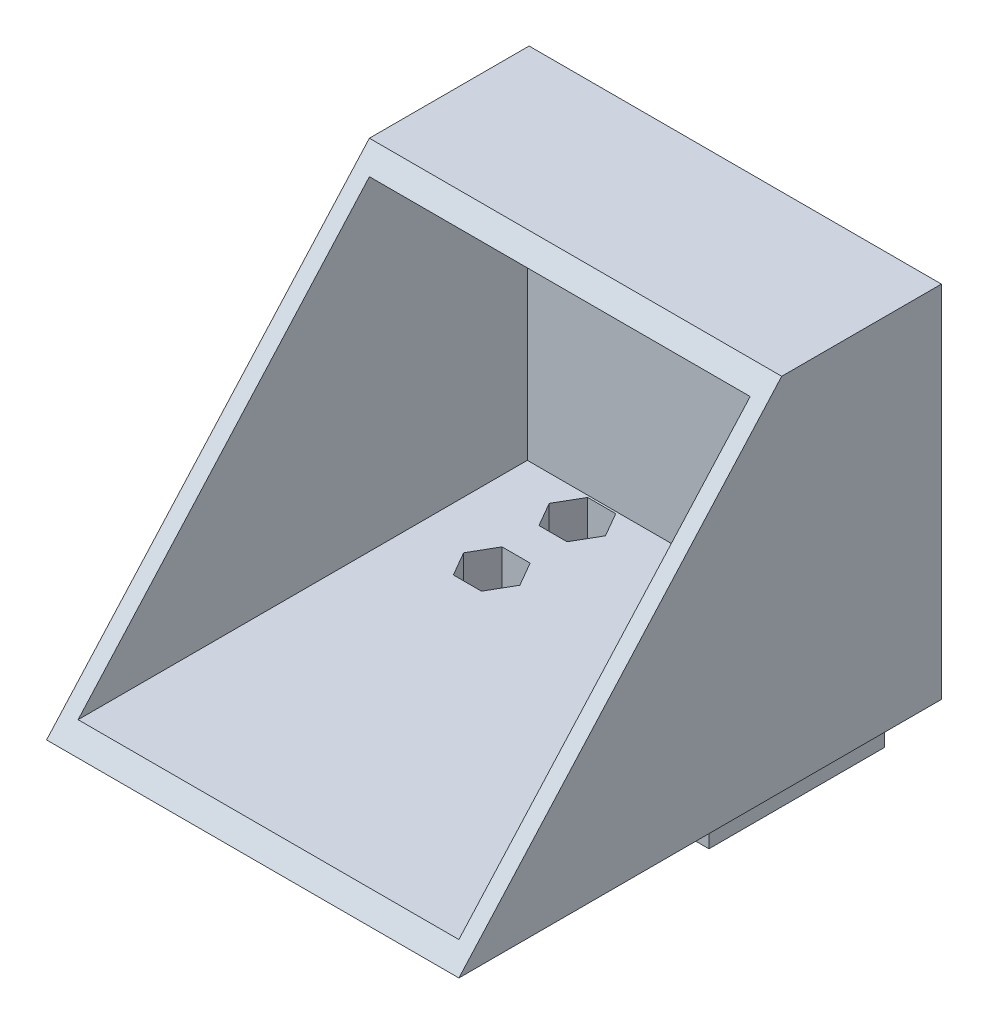
SolidWorks part; units mm, degrees
ref_plane "前视基准面" through (0, 0, 0) normal (0, 0, 1) x (1, 0, 0)
ref_plane "上视基准面" through (0, 0, 0) normal (0, 1, 0) x (1, 0, 0)
ref_plane "右视基准面" through (0, 0, 0) normal (1, 0, 0) x (0, 0, -1)
other "Configuration Table"
ref_plane "基准面1" through (21.7, 0, 0) normal (1, 0, 0) x (0, 0, -1)
sketch "草图1" plane through (21.7, 0, 0) normal (1, 0, 0) x (0, 0, -1)
  line L0 (-18.2051, 8) -> (-18.2051, 49)
  line L1 (-18.2051, 49) -> (-55, 8)
  line L2 (-55, 8) -> (-18.2051, 8)
extrude "凸台-拉伸1" add sketch "草图1" against normal blind 43.4
sketch "草图2" plane through (-21.7, 0, 0) normal (-1, 0, 0) x (0, 0, 1)
  line L0 (18.2051, 8) -> (18.2051, 49)
  line L1 (18.2051, 49) -> (55, 8)
  line L2 (55, 8) -> (18.2051, 8)
extrude "凸台-拉伸2" add sketch "草图2" along normal blind 1.8
sketch "草图3" plane through (21.7, 0, 0) normal (1, 0, 0) x (0, 0, -1)
  line L0 (-18.2051, 8) -> (-18.2051, 47)
  line L1 (-18.2051, 47) -> (-20, 47)
  line L2 (-20, 47) -> (-55, 8)
  line L3 (-55, 8) -> (-18.2051, 8)
extrude "切除-拉伸1" cut sketch "草图3" against normal blind 43.4
sketch "草图4" plane through (-21.7, 0, 0) normal (1, 0, 0) x (0, 0, -1)
  line L0 (-18.2051, 10) -> (-18.2051, 8)
  line L1 (-18.2051, 8) -> (-55, 8)
  line L2 (-55, 8) -> (-53.2051, 10)
  line L3 (-53.2051, 10) -> (-18.2051, 10)
extrude "凸台-拉伸3" add sketch "草图4" along normal blind 43.4
sketch "草图5" plane through (0, 0, 18.2051) normal (0, 0, -1) x (-1, 0, 0)
  line L0 (21.7, 10) -> (21.7, 47)
  line L1 (21.7, 47) -> (-21.7, 47)
  line L2 (-21.7, 47) -> (-21.7, 49)
  line L3 (-21.7, 49) -> (23.5, 49)
  line L4 (23.5, 49) -> (23.5, 8)
  line L5 (23.5, 8) -> (-21.7, 8)
  line L6 (-21.7, 8) -> (-21.7, 10)
  line L7 (-21.7, 10) -> (21.7, 10)
extrude "凸台-拉伸4" add sketch "草图5" along normal blind 16.2051
sketch "草图6" plane through (0, 0, 2) normal (0, 0, -1) x (-1, 0, 0)
  line L0 (-21.7, 8) -> (-21.7, 49)
  line L1 (-21.7, 49) -> (23.5, 49)
  line L2 (23.5, 49) -> (23.5, 8)
  line L3 (23.5, 8) -> (-21.7, 8)
extrude "凸台-拉伸5" add sketch "草图6" along normal blind 2
sketch "草图7" plane through (0, 8, 0) normal (0, -1, 0) x (1, 0, 0)
  line L0 (-17, 0) -> (-17, 20)
  line L1 (-17, 20) -> (17, 20)
  line L2 (17, 20) -> (17, 0)
  line L3 (17, 0) -> (-17, 0)
extrude "凸台-拉伸6" add sketch "草图7" along normal blind 8
sketch "草图10" plane through (21.7, 0, 0) normal (1, 0, 0) x (0, 0, -1)
  line L0 (0, 49) -> (0, 8)
  line L1 (0, 8) -> (-55, 8)
  line L2 (-55, 8) -> (-18.2051, 49)
  line L3 (-18.2051, 49) -> (0, 49)
extrude "凸台-拉伸7" add sketch "草图10" along normal blind 1.8
hole_wizard "Ø3.3 (3.3) 直径孔2" positions "草图16" profile "草图15" hole size "Ø3.3" standard "ANSI Metric"
sketch "草图16" plane through (0, 0, 0) normal (0, -1, 0) x (-1, 0, 0)
  point P0 (13, -5)
  point P1 (13, -14.757)
sketch "草图15" plane through (-13, 0, 5) normal (1, 0, 0) x (0, 0, -1)
  line L0 (0, 0) -> (0, 10)
  line L1 (0, 10) -> (1.65, 10)
  line L2 (1.65, 10) -> (1.65, 0)
  line L5 (1.65, 0) -> (0, 0)
  line L11 (0, -6.35) -> (0, 107.95) construction
  dimension "通孔孔直径" = 3.3
  dimension "通孔孔深度" = 10
hole_wizard "Ø16.0 (16) 直径孔1" positions "草图18" profile "草图17" hole size "Ø16.0" standard "ANSI Metric"
sketch "草图18" plane through (0, 0, 0) normal (0, 0, -1) x (-1, 0, 0)
  point P0 (0, 0)
sketch "草图17" plane through (0, 0, 0) normal (1, 0, 0) x (0, 1, 0)
  line L0 (0, 0) -> (0, 55)
  line L1 (0, 55) -> (8, 55)
  line L2 (8, 55) -> (8, 0)
  line L5 (8, 0) -> (0, 0)
  line L11 (0, -6.35) -> (0, 107.95) construction
  dimension "通孔孔直径" = 16
  dimension "通孔孔深度" = 55
sketch "草图19" plane through (0, 10, 0) normal (0, 1, 0) x (1, 0, 0)
  line L0 (-9.7957, -14.757) -> (-11.3979, -11.982)
  line L1 (-9.7957, -5) -> (-11.3979, -2.225)
  line L2 (-11.3979, -2.225) -> (-14.6021, -2.225)
  line L3 (-14.6021, -2.225) -> (-16.2043, -5)
  line L4 (-16.2043, -5) -> (-14.6021, -7.775)
  line L5 (-14.6021, -7.775) -> (-11.3979, -7.775)
  line L6 (-11.3979, -7.775) -> (-9.7957, -5)
  line L7 (-11.3979, -11.982) -> (-14.6021, -11.982)
  line L8 (-14.6021, -11.982) -> (-16.2043, -14.757)
  line L9 (-16.2043, -14.757) -> (-14.6021, -17.532)
  line L10 (-14.6021, -17.532) -> (-11.3979, -17.532)
  line L11 (-11.3979, -17.532) -> (-9.7957, -14.757)
  circle A0 centre (-13, -14.757) radius 1.65 construction
  circle A1 centre (-13, -5) radius 1.65 construction
  circle A2 centre (-13, -14.757) radius 1.65
  circle A3 centre (-13, -5) radius 1.65
  circle A4 centre (-13, -5) radius 2.775 construction
  dimension "D1" = 5.55
  dimension "D2" = 2
extrude "切除-拉伸6" cut sketch "草图19" against normal blind 5
ref_plane "基准面2" through (0, 0, 0) normal (-1, 0, 0) x (0, 0, 1)
mirror "镜向1" about plane through (0, 0, 0) normal (-1, 0, 0) of "切除-拉伸6", "Ø3.3 (3.3) 直径孔2"
